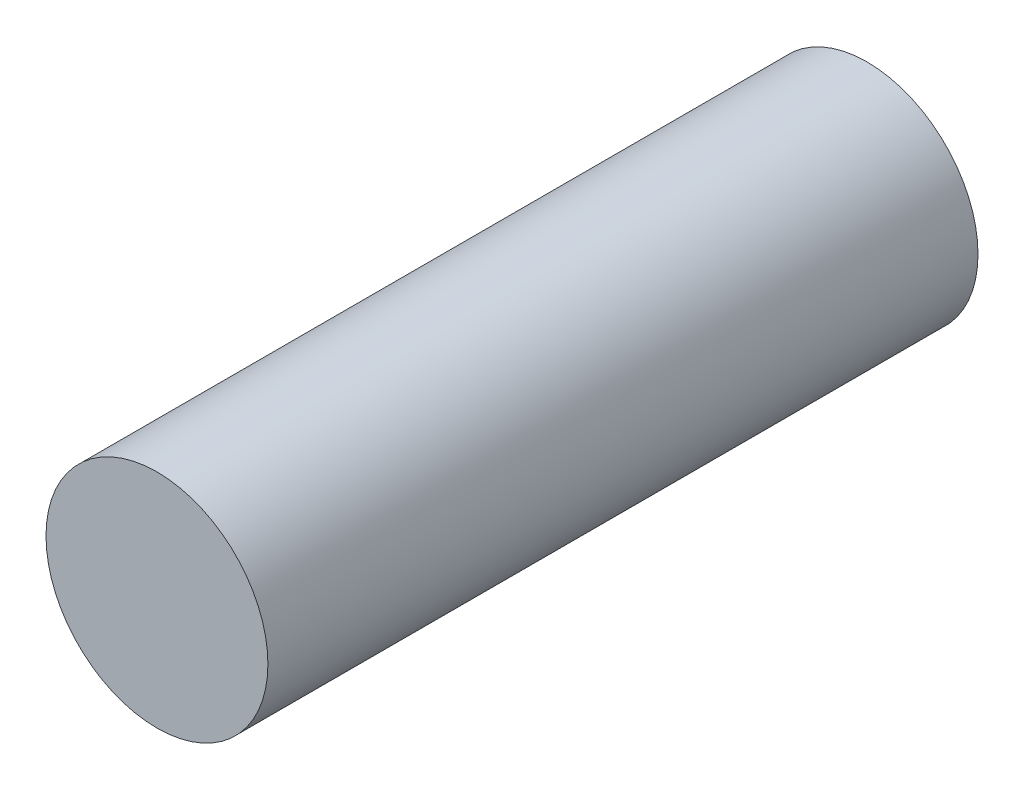
SolidWorks part; units mm, degrees
ref_plane "Front Plane" through (0, 0, 0) normal (0, 0, 1) x (1, 0, 0)
ref_plane "Top Plane" through (0, 0, 0) normal (0, 1, 0) x (1, 0, 0)
ref_plane "Right Plane" through (0, 0, 0) normal (1, 0, 0) x (0, 0, -1)
sketch "Sketch1" plane through (0, 0, 0) normal (0, 0, 1) x (1, 0, 0)
  circle A0 centre (0, 0) radius 2.5
extrude "Boss-Extrude1" add sketch "Sketch1" along normal mid plane 16
